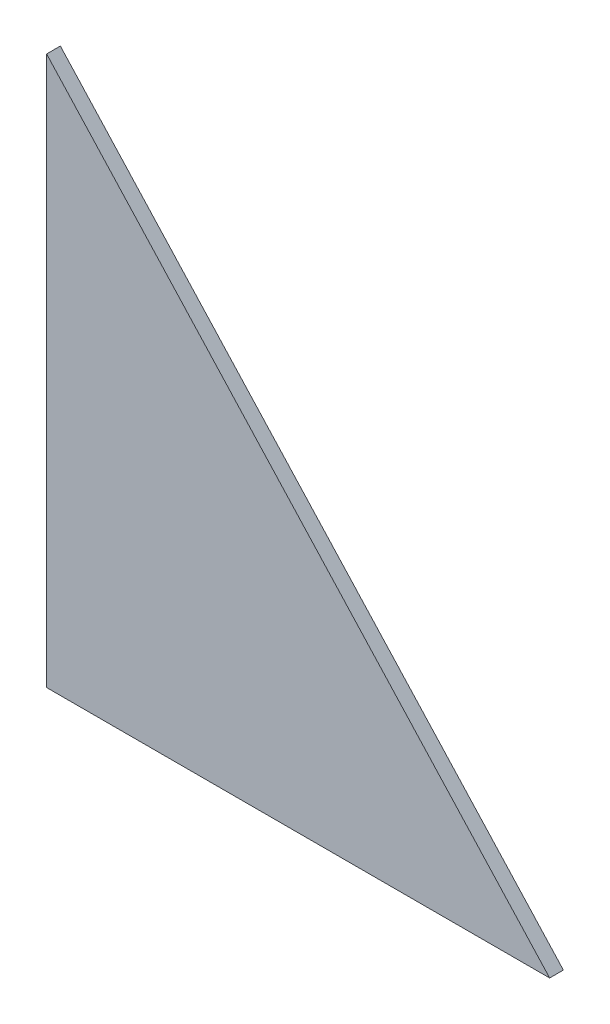
SolidWorks part; units mm, degrees
material "Chapa F.F 1020 - 1,5 mm"
ref_plane "Plano frontal" through (0, 0, 0) normal (0, 0, 1) x (1, 0, 0)
ref_plane "Plano superior" through (0, 0, 0) normal (0, 1, 0) x (1, 0, 0)
ref_plane "Plano direito" through (0, 0, 0) normal (1, 0, 0) x (0, 0, -1)
sketch "Esboço1" plane through (0, 0, 0) normal (0, 0, 1) x (1, 0, 0)
  line L0 (0, 60) -> (0, -62.7329) construction
  line L1 (-64.8194, 0) -> (55, 0) construction
  line L2 (0, 0) -> (0, 60)
  line L3 (0, 60) -> (55, 0)
  line L4 (55, 0) -> (0, 0)
  dimension "D1" = 55
  dimension "D2" = 60
extrude "Ressalto-extrusão1" add sketch "Esboço1" along normal blind 1.5
